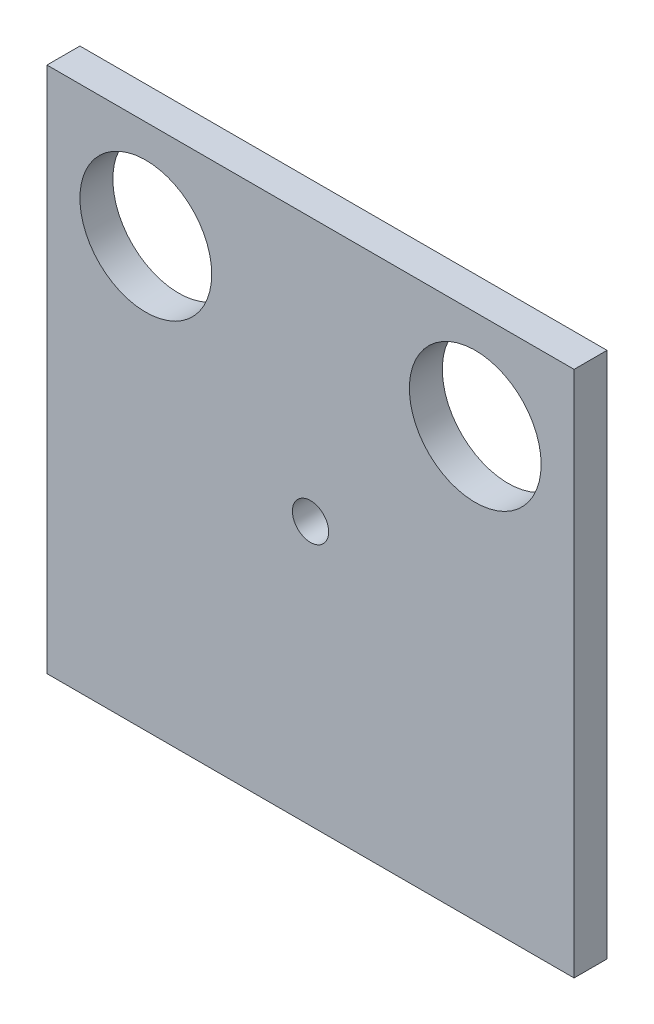
SolidWorks part; units mm, degrees
material "6061 Alloy"
ref_plane "Front Plane" through (0, 0, 0) normal (0, 0, 1) x (1, 0, 0)
ref_plane "Top Plane" through (0, 0, 0) normal (0, 1, 0) x (1, 0, 0)
ref_plane "Right Plane" through (0, 0, 0) normal (1, 0, 0) x (0, 0, -1)
sketch "Sketch1" plane through (0, 0, 0) normal (0, 0, 1) x (1, 0, 0)
  line L0 (19.05, 82.55) -> (82.55, 82.55) construction
  line L1 (0, 0) -> (101.6, 0)
  line L2 (0, 0) -> (0, 101.6)
  line L3 (0, 101.6) -> (101.6, 101.6)
  line L4 (101.6, 0) -> (101.6, 101.6)
  line L5 (50.8, 101.6) -> (50.8, 82.55) construction
  line L6 (0, 101.6) -> (101.6, 0) construction
  circle A0 centre (19.05, 82.55) radius 12.7
  circle A1 centre (82.55, 82.55) radius 12.7
  circle A2 centre (50.8, 50.8) radius 3.4925
  dimension "D4" = 25.4
  dimension "D5" = 6.985
  dimension "D1" = 101.6
  dimension "D2" = 19.05
  dimension "D3" = 63.5
extrude "Boss-Extrude1" add sketch "Sketch1" along normal blind 6.35
ref_plane "Plane1" through (50.8, 0, 0) normal (1, 0, 0) x (0, 0, -1)
